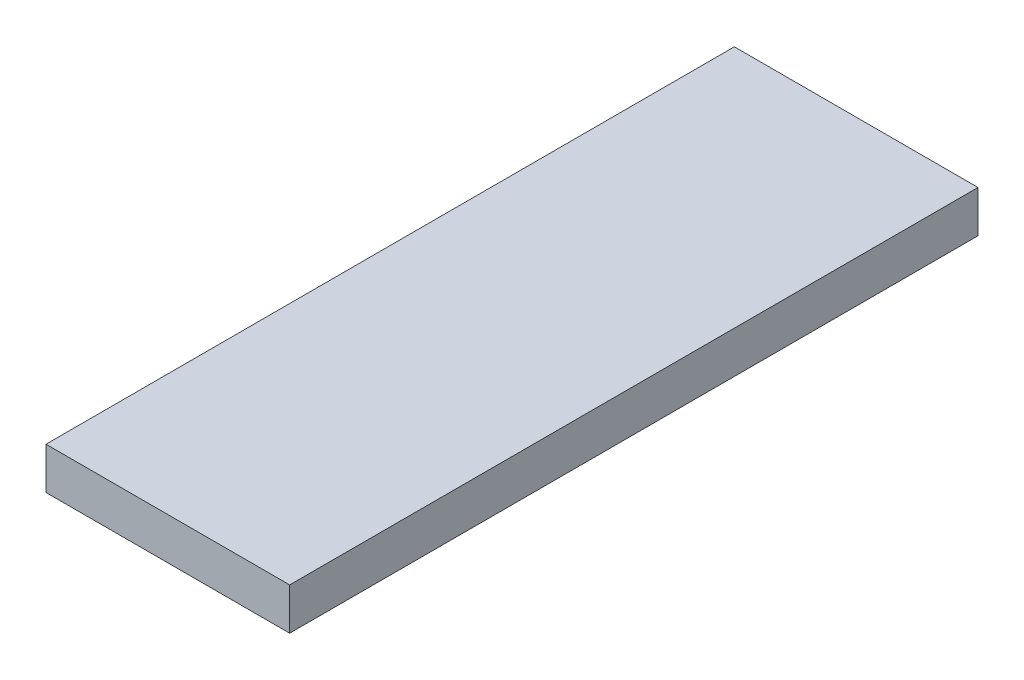
SolidWorks part; units mm, degrees
ref_plane "Front Plane" through (0, 0, 0) normal (0, 0, 1) x (1, 0, 0)
ref_plane "Top Plane" through (0, 0, 0) normal (0, 1, 0) x (1, 0, 0)
ref_plane "Right Plane" through (0, 0, 0) normal (1, 0, 0) x (0, 0, -1)
sketch "Sketch1" plane through (0, 0, 0) normal (0, 0, 1) x (1, 0, 0)
  line L0 (-23.3607, 16.4959) -> (16.6393, -23.5041)
  line L1 (-23.3607, 16.4959) -> (16.6393, 16.4959)
  line L2 (-23.3607, 16.4959) -> (-23.3607, -23.5041)
  line L3 (-23.3607, -23.5041) -> (16.6393, -23.5041)
  line L4 (16.6393, 16.4959) -> (16.6393, -23.5041)
  circle A0 centre (-3.3607, -3.5041) radius 16.25
  circle A1 centre (-3.3607, 12.7459) radius 1.6
  circle A2 centre (12.8893, -3.5041) radius 1.6
  circle A3 centre (-3.3607, -19.7541) radius 1.6
  circle A4 centre (-19.6107, -3.5041) radius 1.6
  circle A5 centre (-3.3607, -3.5041) radius 11.25
  point P17 (-3.3607, -3.5041)
  dimension "D3" = 32.5
  dimension "D4" = 3.2
  dimension "D6" = 22.5
  dimension "D1" = 40
  dimension "D2" = 40
  dimension "D5" = 4
extrude "Boss-Extrude1" add sketch "Sketch1" along normal blind 8 contours A2 A0 L0 L4 L1 A1 | A4 A0 L0 L2 L3 A3 | A4 A0 A3 L0 | A2 A0 A1 L0
sketch "Sketch2" plane through (0, 0, 8) normal (0, 0, 1) x (1, 0, 0)
chamfer "Chamfer2" distance 1 angle 45 4 edges at (14.4893, -3.5041, 0) (-1.7607, -19.7541, 0) (-18.0107, -3.5041, 0) (-1.7607, 12.7459, 0)
chamfer "Chamfer4" distance 1.3 angle 45 1 edges at (7.8893, -3.5041, 0)
sketch "Sketch3" plane through (0, 0, 8) normal (0, 0, 1) x (1, 0, 0)
  line L0 (1.229, 16.4959) -> (16.6393, 16.4959)
  line L1 (-23.3607, 16.4959) -> (-7.9504, 16.4959)
  line L2 (-23.3607, 16.4959) -> (-23.3607, 1.0856)
  line L3 (-23.3607, -23.5041) -> (-7.9504, -23.5041)
  line L4 (16.6393, 16.4959) -> (16.6393, -23.5041)
  line L6 (-7.9504, -16.0041) -> (-7.9504, -23.5041)
  line L8 (1.229, -16.0041) -> (1.229, -23.5041)
  line L9 (1.229, -23.5041) -> (16.6393, -23.5041)
  line L12 (-15.8607, 1.0856) -> (-23.3607, 1.0856)
  line L14 (-15.8607, -8.0938) -> (-23.3607, -8.0938)
  line L18 (1.229, 8.9959) -> (1.229, 16.4959)
  line L20 (-7.9504, 8.9959) -> (-7.9504, 16.4959)
  line L24 (9.1393, -8.0938) -> (16.6393, -8.0938)
  line L26 (9.1393, 1.0856) -> (16.6393, 1.0856)
  line L27 (16.6393, -8.0938) -> (16.6393, 1.0856)
  line L28 (-15.8607, 1.0856) -> (-13.6318, 1.0856)
  line L29 (-13.6318, 1.0856) -> (-13.6318, -8.0938)
  line L30 (-13.6318, -8.0938) -> (-15.8607, -8.0938)
  line L31 (1.229, 8.9959) -> (1.229, 6.7671)
  line L32 (1.229, 6.7671) -> (-7.9504, 6.7671)
  line L33 (-7.9504, 6.7671) -> (-7.9504, 8.9959)
  line L34 (9.1393, -8.0938) -> (6.9105, -8.0938)
  line L35 (6.9105, -8.0938) -> (6.9105, 1.0856)
  line L36 (6.9105, 1.0856) -> (9.1393, 1.0856)
  line L37 (-7.9504, -16.0041) -> (-7.9504, -13.7753)
  line L38 (-7.9504, -13.7753) -> (1.229, -13.7753)
  line L39 (1.229, -13.7753) -> (1.229, -16.0041)
  line L42 (-23.3607, -8.0938) -> (-23.3607, -23.5041)
  circle A0 centre (-3.3607, -3.5041) radius 11.25 construction
  point P6 (-3.3607, -19.7541)
  point P15 (-19.6107, -3.5041)
  point P20 (-3.3607, 12.7459)
  point P25 (12.8893, -3.5041)
  point P30 (-3.3607, -3.5041)
  point P47 (-3.3607, -3.5041)
  line M12 (-23.3607, -23.5041) -> (16.6393, -23.5041)
  line M13 (16.6393, -23.5041) -> (16.6393, 16.4959)
  line M14 (16.6393, 16.4959) -> (-23.3607, 16.4959)
  line M15 (-23.3607, 16.4959) -> (-23.3607, -23.5041)
  circle M16 centre (-3.3607, -3.5041) radius 11.25
  dimension "D1" = 4
  dimension "D2" = 4
extrude "Boss-Extrude2" add sketch "Sketch3" along normal blind 5 contours L6 L37 L30 L14 M16 M15 M12 | L33 L20 L12 L28 M16 M14 M15 | L36 L26 L18 L31 M16 M13 M14 | L39 L8 L24 L34 M16 M12 M13
sketch "Sketch5" plane through (16.6393, 0, 0) normal (1, 0, 0) x (0, 0, -1)
  line L0 (0, -23.5041) -> (0, -127.9341) construction
  line L1 (-13, 16.4959) -> (-23, 16.4959)
  line L2 (-33, 6.4959) -> (-33, -79.8644)
  line L4 (-33, -127.9341) -> (0, -127.9341)
  line L5 (0, -127.9341) -> (80, -127.9341)
  line L6 (-13, 16.4959) -> (-13, -23.5041)
  line L7 (-13, -23.5041) -> (0, -23.5041)
  line L8 (-33, -79.8644) -> (-33, -127.9341)
  arc A0 (0, -23.5041) -> (80, -127.9341) centre (108.1602, -23.5041) ccw
  arc A2 (-23, 16.4959) -> (-33, 6.4959) centre (-23, 6.4959) ccw
  point P15 (-33, -83.5041)
  point P18 (-33, 16.4959)
  dimension "D7" = 10
  dimension "D1" = 104.43
  dimension "D2" = 20
  dimension "D3" = 86.3603
  dimension "D4" = 100
  dimension "D5" = 80
extrude "Boss-Extrude3" add sketch "Sketch5" against normal up to surface (40 mm away) up to face at (-23.3607, -3.5041, 8.5)
sketch "Sketch6" plane through (16.6393, 0, 0) normal (1, 0, 0) x (0, 0, -1)
  line L0 (-13, 1.0856) -> (-20, 1.0856)
  line L1 (-20, 1.0856) -> (-20, -8.0938)
  line L2 (-20, -8.0938) -> (-13, -8.0938)
  line L3 (-13, -8.0938) -> (-13, 1.0856)
  dimension "D1" = 7
extrude "Cut-Extrude1" cut sketch "Sketch6" against normal through all both and the other way through all
sketch "Sketch7" plane through (0, 16.4959, 0) normal (0, 1, 0) x (1, 0, 0)
  line L0 (-7.9504, -13) -> (-7.9504, -19)
  line L1 (-7.9504, -19) -> (1.229, -19)
  line L2 (1.229, -19) -> (1.229, -13)
  line L3 (1.229, -13) -> (-7.9504, -13)
  dimension "D1" = 6
extrude "Cut-Extrude2" cut sketch "Sketch7" against normal up to vertex and the other way through all
sketch "Sketch8" plane through (0, -127.9341, 0) normal (0, -1, 0) x (1, 0, 0)
  line L0 (-3.1607, -80) -> (-3.1607, 33) construction
  line L1 (-23.3607, -80) -> (16.6393, -80) construction
  line L3 (4.9893, -32.9382) -> (1.1393, -26.01)
  line L4 (4.8393, -52.9868) -> (0.8393, -46.0586)
  line L5 (0.8393, -46.0586) -> (-7.1607, -46.0586)
  line L6 (-7.1607, -46.0586) -> (-11.1607, -52.9868)
  line L7 (-11.1607, -52.9868) -> (-7.1607, -59.915)
  line L8 (-7.1607, -59.915) -> (0.8393, -59.915)
  line L9 (0.8393, -59.915) -> (4.8393, -52.9868)
  line L10 (1.1393, -26.01) -> (-7.1607, -26.01)
  line L11 (-7.1607, -26.01) -> (-11.0107, -32.9382)
  line L12 (-11.0107, -32.9382) -> (-7.0107, -39.8664)
  line L13 (-7.0107, -39.8664) -> (0.9893, -39.8664)
  line L14 (0.9893, -39.8664) -> (4.9893, -32.9382)
  line L15 (4.8393, -13.029) -> (0.8393, -6.1008)
  line L16 (0.8393, -6.1008) -> (-7.1607, -6.1008)
  line L17 (-7.1607, -6.1008) -> (-11.1607, -13.029)
  line L18 (-11.1607, -13.029) -> (-7.1607, -19.9572)
  line L19 (-7.1607, -19.9572) -> (0.8393, -19.9572)
  line L20 (0.8393, -19.9572) -> (4.8393, -13.029)
  line L21 (4.8393, 6.9718) -> (0.8393, 13.9)
  line L22 (0.8393, 13.9) -> (-7.1607, 13.9)
  line L23 (-7.1607, 13.9) -> (-11.1607, 6.9718)
  line L24 (-11.1607, 6.9718) -> (-7.1607, 0.0436)
  line L25 (-7.1607, 0.0436) -> (0.8393, 0.0436)
  line L26 (0.8393, 0.0436) -> (4.8393, 6.9718)
  line L28 (16.6393, 33) -> (16.6393, -80) construction
  line L29 (-3.0107, -39.8664) -> (-3.0107, -26.01) construction
  circle A0 centre (-3.1607, -52.9868) radius 6.9282 construction
  dimension "D1" = 8
  dimension "D2" = 20.085
  dimension "D4" = 8
  dimension "D5" = 19.8
  dimension "D3" = 8
  dimension "D6" = 53.99
  dimension "D7" = 19.65
  dimension "D8" = 73.8992
  dimension "D9" = 93.9
extrude "Boss-Extrude4" add sketch "Sketch8" along normal blind 10
sketch "Sketch12" plane through (16.6393, 0, 0) normal (1, 0, 0) x (0, 0, -1)
  line L1 (-33, 16.4959) -> (75.0119, 16.4959)
  line L2 (-33, 16.4959) -> (-33, -121.0646)
  line L3 (-33, -121.0646) -> (75.0119, -121.0646)
  line L4 (75.0119, 16.4959) -> (75.0119, -121.0646)
extrude "Cut-Extrude4" cut sketch "Sketch12" against normal through all
sketch "Sketch13" plane through (0, 0, 33) normal (0, 0, 1) x (1, 0, 0)
  line L1 (-23.3607, -121.0646) -> (16.6393, -121.0646)
  line L2 (-23.3607, -121.0646) -> (-23.3607, -127.9341)
  line L3 (-23.3607, -127.9341) -> (16.6393, -127.9341)
  line L4 (16.6393, -121.0646) -> (16.6393, -127.9341)
  line M5 (16.6393, -121.0646) -> (-23.3607, -121.0646)
  line M6 (-23.3607, -121.0646) -> (-23.3607, -127.9341)
  line M7 (-23.3607, -127.9341) -> (16.6393, -127.9341)
  line M8 (16.6393, -127.9341) -> (16.6393, -121.0646)
extrude "Boss-Extrude7" add sketch "Sketch13" against normal through all contours M8 M5 M6 M7
